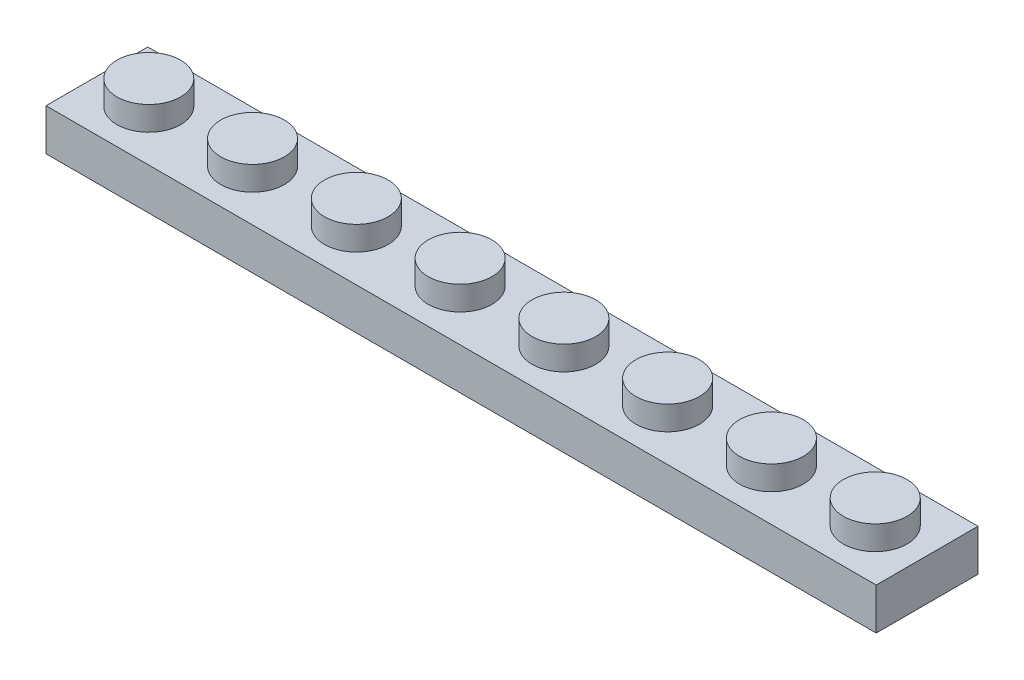
SolidWorks part; units mm, degrees
ref_plane "Front Plane" through (0, 0, 0) normal (0, 0, 1) x (1, 0, 0)
ref_plane "Top Plane" through (0, 0, 0) normal (0, 1, 0) x (1, 0, 0)
ref_plane "Right Plane" through (0, 0, 0) normal (1, 0, 0) x (0, 0, -1)
sketch "Sketch1" plane through (0, 0, 0) normal (0, 1, 0) x (1, 0, 0)
  line L1 (-31.925, 3.915) -> (31.925, 3.915)
  line L2 (-31.925, 3.915) -> (-31.925, -3.915)
  line L3 (-31.925, -3.915) -> (31.925, -3.915)
  line L4 (31.925, 3.915) -> (31.925, -3.915)
  line L5 (-31.925, 3.915) -> (31.925, -3.915) construction
  line L6 (-31.925, -3.915) -> (31.925, 3.915) construction
  point P0 (0, 0)
  dimension "D1" = 7.83
  dimension "D2" = 63.85
extrude "Boss-Extrude1" add sketch "Sketch1" against normal blind 3.2
sketch "Sketch2" plane through (0, 0, 0) normal (0, 1, 0) x (1, 0, 0)
  line L1 (-31.925, 3.915) -> (-31.925, -3.915) construction
  line L3 (31.925, 3.915) -> (-31.925, 3.915) construction
  circle A0 centre (-27.9344, 0) radius 2.45
  circle A1 centre (-19.9531, 0) radius 2.45
  circle A2 centre (-11.9719, 0) radius 2.45
  circle A3 centre (-3.9906, 0) radius 2.45
  circle A4 centre (3.9906, 0) radius 2.45
  circle A5 centre (11.9719, 0) radius 2.45
  circle A6 centre (19.9531, 0) radius 2.45
  circle A7 centre (27.9344, 0) radius 2.45
  dimension "D1" = 4.9
  dimension "D5" = 7.9813
  dimension "D2" = 3.9906
  dimension "D3" = 8
  dimension "D4" = 3.915
extrude "Boss-Extrude2" add sketch "Sketch2" along normal blind 1.85
shell "Shell1" thickness 1.6
sketch "Sketch3" plane through (0, -1.6, 0) normal (0, -1, 0) x (1, 0, 0)
  line L1 (-31.925, -3.915) -> (-31.925, 3.915) construction
  line L2 (31.925, -3.915) -> (-31.925, -3.915) construction
  circle A0 centre (-23.9438, 0) radius 1.5
  circle A1 centre (-23.9438, 0) radius 0.75
  circle A2 centre (-15.9625, 0) radius 0.75
  circle A3 centre (-15.9625, 0) radius 1.5
  circle A4 centre (-7.9813, 0) radius 0.75
  circle A5 centre (-7.9813, 0) radius 1.5
  circle A6 centre (0, 0) radius 0.75
  circle A7 centre (0, 0) radius 1.5
  circle A8 centre (7.9812, 0) radius 0.75
  circle A9 centre (7.9812, 0) radius 1.5
  circle A10 centre (15.9625, 0) radius 0.75
  circle A11 centre (15.9625, 0) radius 1.5
  circle A12 centre (23.9437, 0) radius 0.75
  circle A13 centre (23.9437, 0) radius 1.5
  dimension "D1" = 7.9813
  dimension "D3" = 3
  dimension "D4" = 1.5
  dimension "D6" = 7.9813
  dimension "D2" = 3.915
  dimension "D5" = 7
extrude "Boss-Extrude3" add sketch "Sketch3" along normal offset from surface (1.4 mm away) 0.2 up to face at (0, -3.2, 0)
